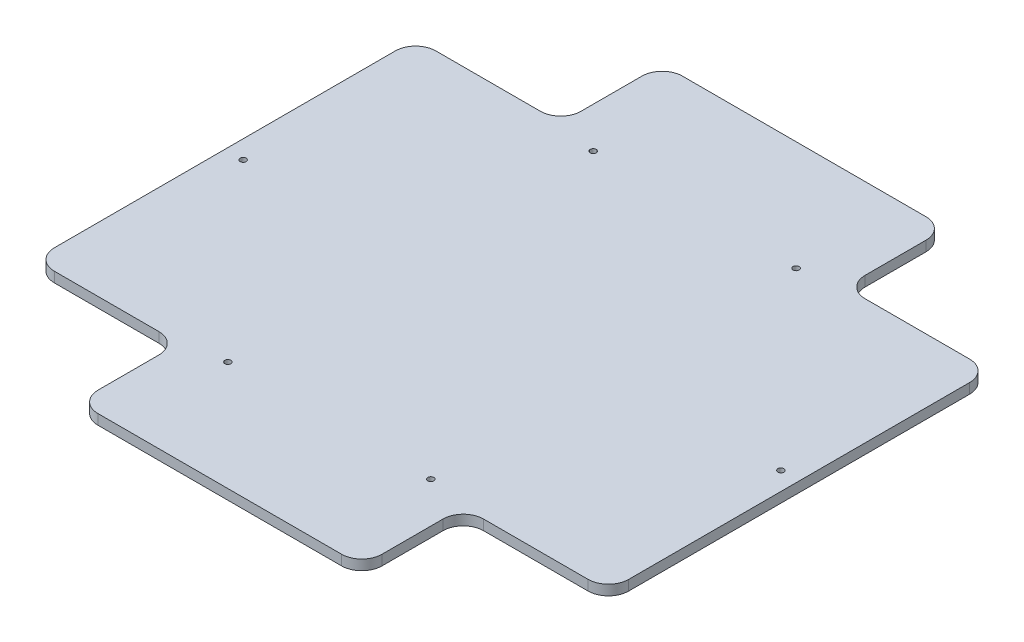
SolidWorks part; units mm, degrees
ref_plane "前视基准面" through (0, 0, 0) normal (0, 0, 1) x (1, 0, 0)
ref_plane "上视基准面" through (0, 0, 0) normal (0, 1, 0) x (1, 0, 0)
ref_plane "右视基准面" through (0, 0, 0) normal (1, 0, 0) x (0, 0, -1)
sketch "草图1" plane through (0, 0, 0) normal (0, 1, 0) x (1, 0, 0)
  line L1 (-150, 150) -> (150, 150)
  line L2 (-150, 150) -> (-150, -150)
  line L3 (-150, -150) -> (150, -150)
  line L4 (150, 150) -> (150, -150)
  line L5 (-150, 150) -> (150, -150) construction
  line L6 (-150, -150) -> (150, 150) construction
  point P0 (0, 0)
  dimension "D1" = 300
  dimension "D2" = 300
extrude "凸台-拉伸1" add sketch "草图1" along normal blind 5
sketch "草图4" plane through (0, 5, 0) normal (0, 1, 0) x (1, 0, 0)
  line L0 (-88.2513, 95) -> (84.3249, 95)
  line L1 (-132.5, 95) -> (-80.0816, 95) construction
  line L2 (84.3249, 95) -> (73.2525, 170.6967)
  line L3 (73.2525, 170.6967) -> (-48.5435, 170.6967)
  line L4 (-48.5435, 170.6967) -> (-88.2513, 95)
  line L5 (-81.8359, -95) -> (-68.3974, -170.7644)
  line L6 (132.5, -95) -> (79.9184, -95) construction
  line L7 (-68.3974, -170.7644) -> (34.9421, -175.2732)
  line L8 (34.9421, -175.2732) -> (78.7887, -129.2834)
  line L9 (78.7887, -129.2834) -> (78.7887, -95)
  line L10 (78.7887, -95) -> (-81.8359, -95)
extrude "切除-拉伸3" cut sketch "草图4" against normal blind 10
sketch "草图6" plane through (0, 5, 0) normal (0, 1, 0) x (1, 0, 0)
  line L0 (-88.2513, 95) -> (233.5092, 95)
  line L1 (233.5092, 95) -> (223.8657, 204.9232)
  line L2 (223.8657, 204.9232) -> (-177.7149, 215.9443)
  line L3 (-177.7149, 215.9443) -> (-226.621, 137.4191)
  line L4 (-226.621, 137.4191) -> (-226.621, 114.6881)
  line L5 (-88.2513, 95) -> (-226.621, 95)
  line L6 (-226.621, 95) -> (-226.621, 114.6881)
  line L7 (-81.8359, -95) -> (223.8657, -95)
  line L8 (223.8657, -95) -> (223.8657, -205.612)
  line L9 (223.8657, -205.612) -> (-238.3309, -205.612)
  line L10 (-238.3309, -205.612) -> (-238.3309, -95)
  line L11 (-238.3309, -95) -> (-81.8359, -95)
extrude "切除-拉伸5" cut sketch "草图6" against normal blind 10
sketch "草图7" plane through (0, 5, 0) normal (0, 1, 0) x (1, 0, 0)
  line L7 (-141.5, 94) -> (141.5, 94)
  line L8 (-141.5, 94) -> (-141.5, -94)
  line L9 (-141.5, -94) -> (141.5, -94)
  line L10 (141.5, 94) -> (141.5, -94)
extrude "切除-拉伸6" cut sketch "草图7" against normal blind 10 flip side to cut
fillet "圆角1" radius 10 4 edges at (141.5, 2.5, -94) (141.5, 2.5, 94) (-141.5, 2.5, 94) (-141.5, 2.5, -94)
sketch "草图8" plane through (0, 5, 0) normal (0, 1, 0) x (1, 0, 0)
  circle A0 centre (-132.5, 0) radius 1.5
  circle A1 centre (132.5, 0) radius 1.5
extrude "切除-拉伸7" cut sketch "草图8" against normal blind 200
sketch "草图9" plane through (0, 5, 0) normal (0, 1, 0) x (1, 0, 0)
  line L0 (0, 140.2534) -> (0, -186.3217) construction
  line L1 (-220.6808, 0) -> (194.4226, 0) construction
  line L2 (-132.5, 95) -> (-80.0816, 95) construction
  circle A0 centre (-50, 90) radius 1.5
  circle A1 centre (50, 90) radius 1.5
  dimension "D1" = 3
  dimension "D2" = 50
  dimension "D4" = 5
  dimension "D5" = 5
  dimension "D3" = 50
extrude "切除-拉伸8" cut sketch "草图9" against normal blind 200
mirror "镜向1" about plane through (0, 0, 0) normal (0, 0, 1) of "切除-拉伸8"
sketch "草图10" plane through (0, 5, 0) normal (0, 1, 0) x (1, 0, 0)
  line L0 (0, 206.1005) -> (0, -217.37) construction
  line L1 (-131.5, -94) -> (131.5, -94) construction
  line L2 (-70, -94) -> (70, -94)
  line L3 (-70, -94) -> (-70, -144)
  line L4 (-70, -144) -> (70, -144)
  line L5 (70, -94) -> (70, -144)
  line L6 (-196.9384, 0) -> (195.813, 0) construction
  line L7 (-70, 94) -> (-70, 144)
  line L8 (70, 94) -> (70, 144)
  line L9 (-70, 94) -> (70, 94)
  line L10 (-70, 144) -> (70, 144)
  dimension "D1" = 70
  dimension "D2" = 70
  dimension "D3" = 50
extrude "凸台-拉伸2" add sketch "草图10" against normal up to surface (5 mm away) up to face at (-50, 0, 91.5)
fillet "圆角2" radius 10 8 edges at (-70, 2.5, -94) (-70, 2.5, -144) (70, 2.5, -144) (70, 2.5, -94) (-70, 2.5, 94) (-70, 2.5, 144) (70, 2.5, 144) (70, 2.5, 94)
